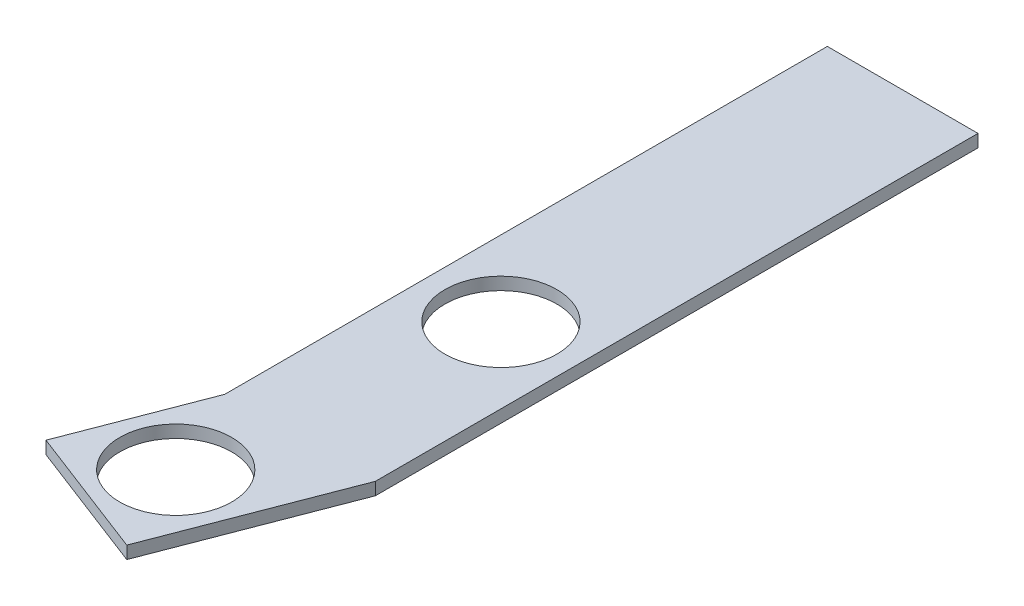
SolidWorks part; units mm, degrees
ref_plane "Front Plane" through (0, 0, 0) normal (0, 0, 1) x (1, 0, 0)
ref_plane "Top Plane" through (0, 0, 0) normal (0, 1, 0) x (1, 0, 0)
ref_plane "Right Plane" through (0, 0, 0) normal (1, 0, 0) x (0, 0, -1)
sketch "Sketch1" plane through (0, 0, 0) normal (0, 1, 0) x (1, 0, 0)
  line L0 (-19.05, -76.2) -> (-31.6053, -108.8404)
  line L1 (-19.05, 76.2) -> (19.05, 76.2)
  line L2 (-19.05, 76.2) -> (-19.05, -76.2)
  line L4 (19.05, 76.2) -> (19.05, -76.2)
  line L5 (-19.05, 76.2) -> (19.05, -76.2) construction
  line L6 (-19.05, -76.2) -> (19.05, 76.2) construction
  line L7 (-31.6053, -108.8404) -> (1.5841, -121.6068)
  line L8 (1.5841, -121.6068) -> (19.05, -76.2)
  line L9 (19.05, -76.2) -> (-19.05, -76.2) construction
  point P0 (0, 0)
  point P6 (-14.8922, -122.5795)
  dimension "D1" = 152.4
  dimension "D2" = 38.1
  dimension "D3" = 35.56
extrude "Boss-Extrude1" add sketch "Sketch1" along normal blind 3.175
sketch "Sketch2" plane through (0, 3.175, 0) normal (0, 1, 0) x (1, 0, 0)
  line L0 (-19.05, -76.2) -> (14.1393, -88.9664) construction
  line L1 (1.5841, -121.6068) -> (19.05, -76.2) construction
  line L2 (-25.3276, -92.5202) -> (7.8617, -105.2866) construction
  line L3 (-19.05, -76.2) -> (-31.6053, -108.8404) construction
  circle A0 centre (-8.733, -98.9034) radius 14.1605
  point P12 (0, 0)
  point P13 (-8.733, -98.9034)
  dimension "D1" = 28.321
extrude "Cut-Extrude1" cut sketch "Sketch2" against normal through all contours A0
sketch "Sketch3" plane through (0, 3.175, 0) normal (0, 1, 0) x (1, 0, 0)
  line L0 (19.05, 76.2) -> (-19.05, 76.2) construction
  circle A0 centre (0, -25.4) radius 14.1605
  dimension "D1" = 28.321
  dimension "D2" = 101.6
extrude "Cut-Extrude2" cut sketch "Sketch3" against normal through all
